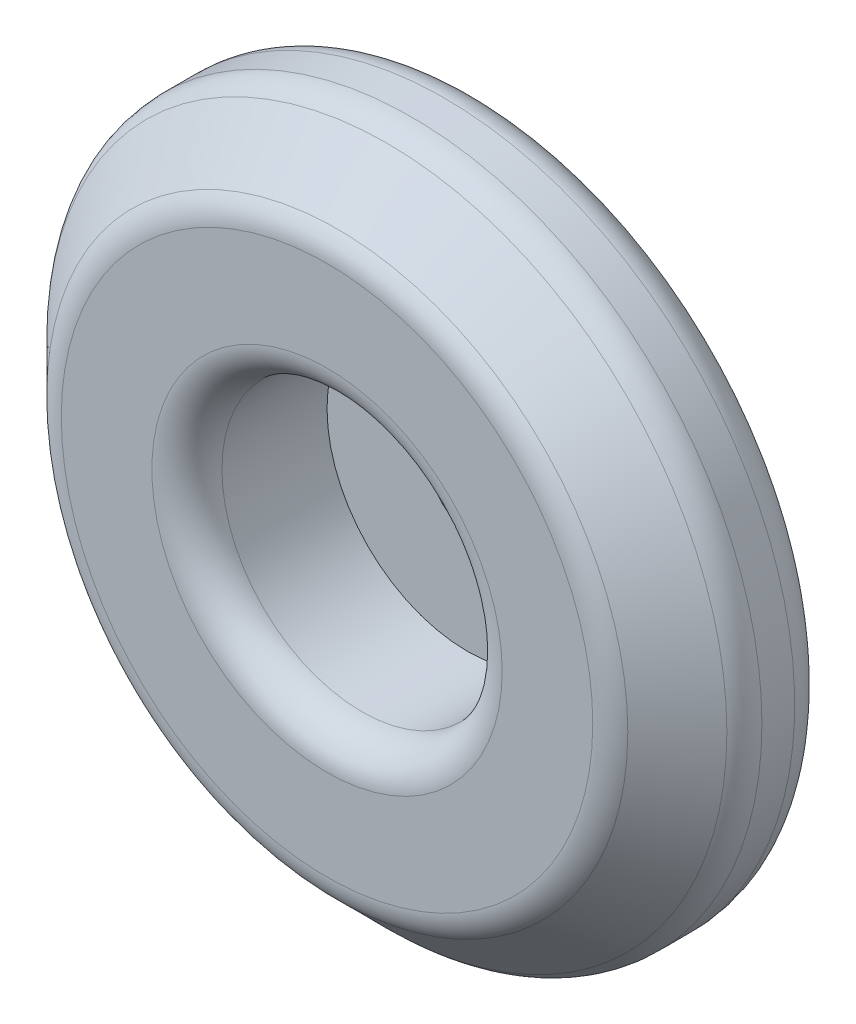
SolidWorks part; units mm, degrees
material "Cast Carbon Steel"
ref_plane "Front Plane" through (0, 0, 0) normal (0, 0, 1) x (1, 0, 0)
ref_plane "Top Plane" through (0, 0, 0) normal (0, 1, 0) x (1, 0, 0)
ref_plane "Right Plane" through (0, 0, 0) normal (1, 0, 0) x (0, 0, -1)
sketch "Sketch1" plane through (0, 0, 0) normal (0, 0, 1) x (1, 0, 0)
  circle A0 centre (0, 0) radius 63.5
  dimension "D1" = 127
extrude "Boss-Extrude1" add sketch "Sketch1" along normal blind 50.8
sketch "Sketch2" plane through (0, 0, 50.8) normal (0, 0, 1) x (1, 0, 0)
  circle A0 centre (0, 0) radius 25.4
  dimension "D1" = 50.8
extrude "Cut-Extrude2" cut sketch "Sketch2" against normal blind 25.4
sketch "Sketch3" plane through (0, 0, 25.4) normal (0, 0, 1) x (1, 0, 0)
  circle A0 centre (0, 0) radius 6.35
  dimension "D1" = 12.7
extrude "Cut-Extrude3" cut sketch "Sketch3" against normal through all
sketch "Sketch4" plane through (0, 0, 0) normal (1, 0, 0) x (0, 0, -1)
  line L0 (0, 63.5) -> (-25.4, 63.5)
  line L1 (0, -63.5) -> (0, 63.5) construction
  line L2 (-25.4, 63.5) -> (0, 6.35)
  line L3 (0, 6.35) -> (0, 63.5)
  line L4 (0, 0) -> (26.5228, 0) construction
  dimension "D1" = 25.4
  dimension "D2" = 6.35
revolve "Cut-Revolve1" cut sketch "Sketch4" angle 360 about L4
ref_plane "Plane1" through (0, 0, 0) normal (0, 0, 1) x (1, 0, 0)
sketch "Sketch6" plane through (0, 0, 0) normal (0, 0, 1) x (1, 0, 0)
  circle A0 centre (0, 0) radius 12.7
  dimension "D1" = 25.4
extrude "Cut-Extrude4" cut sketch "Sketch6" along normal blind 6.35
chamfer "Chamfer1" distance 12.7 angle 45 1 edges at (63.5, 0, 50.8)
fillet "Fillet1" radius 6.35 4 edges at (25.4, 0, 50.8) (50.8, 0, 50.8) (63.5, 0, 38.1) (63.5, 0, 25.4)
